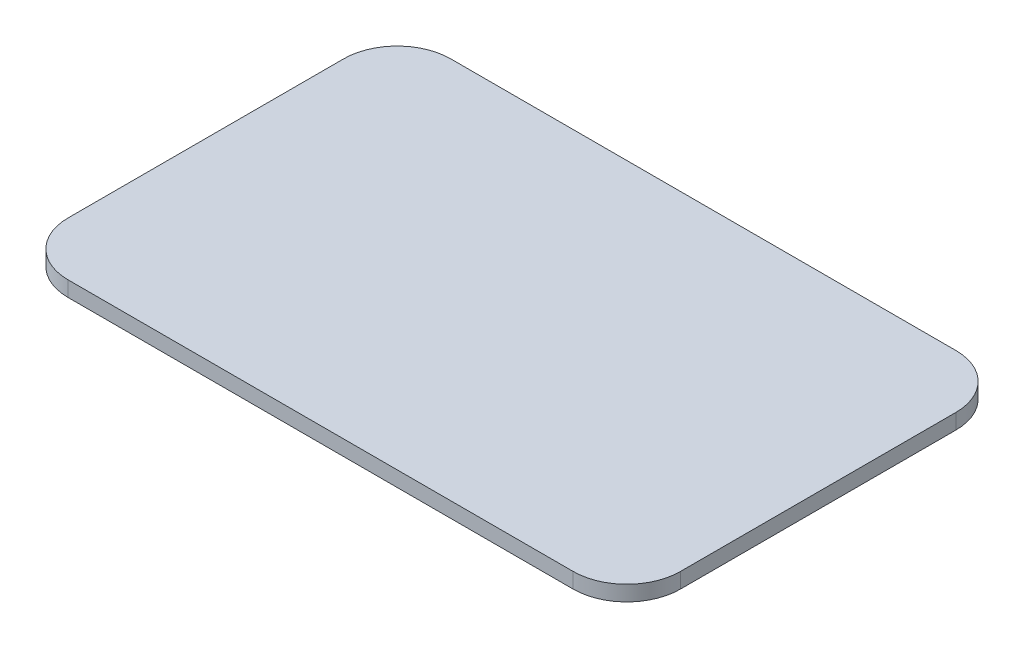
SolidWorks part; units mm, degrees
ref_plane "Front Plane" through (0, 0, 0) normal (0, 0, 1) x (1, 0, 0)
ref_plane "Top Plane" through (0, 0, 0) normal (0, 1, 0) x (1, 0, 0)
ref_plane "Right Plane" through (0, 0, 0) normal (1, 0, 0) x (0, 0, -1)
sketch "Sketch1" plane through (0, 0, 0) normal (0, 1, 0) x (1, 0, 0)
  line L1 (-40, 25) -> (40, 25)
  line L2 (-40, 25) -> (-40, -25)
  line L3 (-40, -25) -> (40, -25)
  line L4 (40, 25) -> (40, -25)
  line L5 (-40, 25) -> (40, -25) construction
  line L6 (-40, -25) -> (40, 25) construction
  point P0 (0, 0)
  point P7 (0, 0)
  dimension "D1" = 80
  dimension "D2" = 50
extrude "Boss-Extrude1" add sketch "Sketch1" along normal blind 2
fillet "Fillet1" radius 7 4 edges at (-40, 1, 25) (-40, 1, -25) (40, 1, -25) (40, 1, 25)
equation "\"Length\"= 90"
equation "\"Width\"= 60"
equation "\"Height\"= 16"
equation "\"R1_main_radius\"= 12"
equation "\"R2\"= 5'Bottom radius"
equation "\"R3\"= 3'Top radius"
equation "\"Wall_Thickness\"= 2'Thickness of the wall"
equation "\"Screw_tower_outer_d\"= 6"
equation "\"Screw_tower_inner_d\"= 3"
equation "\"Tower_D1\"= 10"
equation "\"Tower_D2\"= 5"
equation "\"Tower_height\"= \"Height\" - 2 * \"Wall_Thickness\""
equation "\"Width2\" = \"Width\" - 2 * \"R2\""
equation "\"Length2\" = \"Length\" - 2 * \"R2\""
equation "\"D1@Sketch1\"=\"Length2\""
equation "\"D2@Sketch1\"=\"Width2\""
equation "\"D1@Boss-Extrude1\"=\"Wall_Thickness\""
equation "\"R4\"= 7"
equation "\"D1@Fillet1\"=\"R4\""
